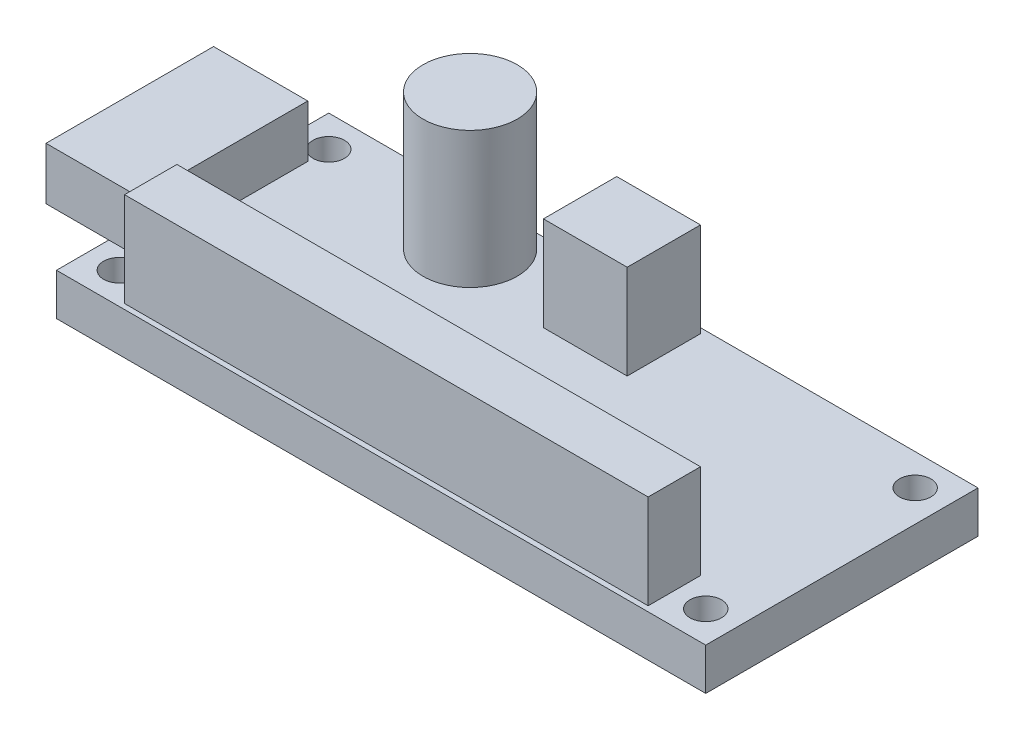
SolidWorks part; units mm, degrees
ref_plane "前视基准面" through (0, 0, 0) normal (0, 0, 1) x (1, 0, 0)
ref_plane "上视基准面" through (0, 0, 0) normal (0, 1, 0) x (1, 0, 0)
ref_plane "右视基准面" through (0, 0, 0) normal (1, 0, 0) x (0, 0, -1)
other "Configuration Table"
sketch "草图1" plane through (0, 0, 0) normal (0, 1, 0) x (1, 0, 0)
  line L1 (0, 0) -> (62, 0)
  line L2 (0, 0) -> (0, 26)
  line L3 (0, 26) -> (62, 26)
  line L4 (62, 0) -> (62, 26)
  dimension "D1" = 62
  dimension "D2" = 26
extrude "凸台-拉伸1" add sketch "草图1" along normal blind 4
sketch "草图2" plane through (0, 4, 0) normal (0, 1, 0) x (1, 0, 0)
  line L0 (0, 24.5) -> (62, 24.5) construction
  line L1 (0, 26) -> (0, 0) construction
  line L2 (62, 0) -> (62, 26) construction
  line L4 (62, 26) -> (0, 26) construction
  line L5 (60.5, 26) -> (60.5, 0) construction
  line L6 (0, 0) -> (62, 0) construction
  line L8 (62, 1.5) -> (0, 1.5) construction
  line L10 (1.5, 0) -> (1.5, 26) construction
  circle A0 centre (3, 23) radius 1.5
  circle A1 centre (3, 3) radius 1.5
  circle A2 centre (59, 3) radius 1.5
  circle A3 centre (59, 23) radius 1.5
  dimension "D5" = 3
  dimension "D1" = 1.5
  dimension "D2" = 1.5
  dimension "D3" = 1.5
  dimension "D4" = 1.5
extrude "切除-拉伸1" cut sketch "草图2" against normal through all
sketch "草图3" plane through (0, 4, 0) normal (0, 1, 0) x (1, 0, 0)
  line L0 (62, 0) -> (62, 26) construction
  line L1 (6, 0.5) -> (56, 0.5)
  line L2 (6, 0.5) -> (6, 5.5)
  line L3 (6, 5.5) -> (56, 5.5)
  line L4 (56, 0.5) -> (56, 5.5)
  line L5 (0, 26) -> (0, 0) construction
  line L6 (0, 0) -> (62, 0) construction
  dimension "D1" = 6
  dimension "D2" = 6
  dimension "D3" = 0.5
  dimension "D4" = 5
extrude "凸台-拉伸2" add sketch "草图3" along normal blind 9
sketch "草图4" plane through (0, 4, 0) normal (0, 1, 0) x (1, 0, 0)
  line L0 (0, 26) -> (0, 0) construction
  line L1 (62, 26) -> (0, 26) construction
  circle A0 centre (18, 21.5) radius 4.5
  dimension "D1" = 9
  dimension "D2" = 18
extrude "凸台-拉伸3" add sketch "草图4" along normal blind 13
sketch "草图5" plane through (0, 4, 0) normal (0, 1, 0) x (1, 0, 0)
  line L0 (62, 26) -> (18, 26) construction
  line L1 (28, 25.5) -> (36, 25.5)
  line L2 (28, 25.5) -> (28, 18.5)
  line L3 (28, 18.5) -> (36, 18.5)
  line L4 (36, 25.5) -> (36, 18.5)
  line L5 (0, 26) -> (0, 0) construction
  dimension "D1" = 0.5
  dimension "D2" = 8
  dimension "D3" = 28
  dimension "D4" = 7
extrude "凸台-拉伸4" add sketch "草图5" along normal blind 9
sketch "草图6" plane through (0, 4, 0) normal (0, 1, 0) x (1, 0, 0)
  line L0 (18, 26) -> (0, 26) construction
  line L1 (-6, 21) -> (3, 21)
  line L2 (-6, 21) -> (-6, 5)
  line L3 (-6, 5) -> (3, 5)
  line L4 (3, 21) -> (3, 5)
  line L5 (0, 0) -> (62, 0) construction
  line L6 (0, 26) -> (0, 0) construction
  dimension "D1" = 5
  dimension "D2" = 5
  dimension "D3" = 3
  dimension "D4" = 9
extrude "凸台-拉伸5" add sketch "草图6" along normal blind 5
